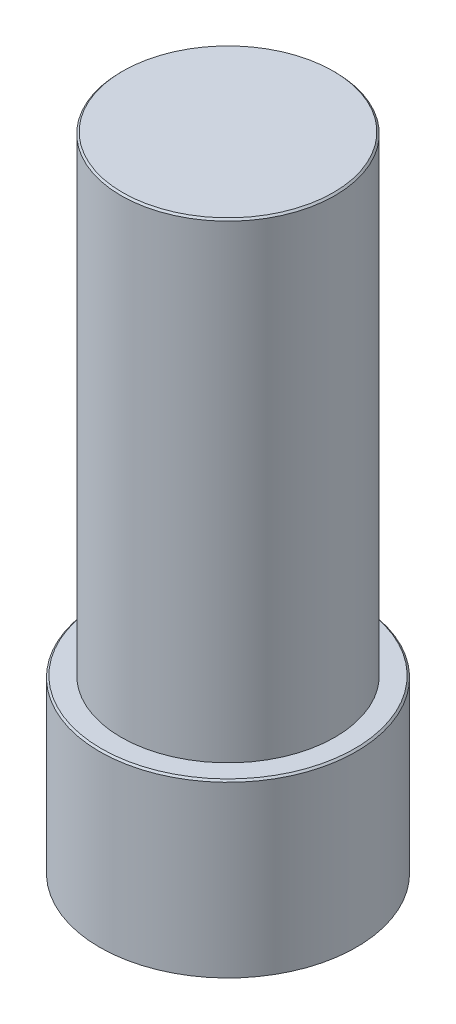
SolidWorks part; units mm, degrees
ref_plane "Plan de face" through (0, 0, 0) normal (0, 0, 1) x (1, 0, 0)
ref_plane "Plan de dessus" through (0, 0, 0) normal (0, 1, 0) x (1, 0, 0)
ref_plane "Plan de droite" through (0, 0, 0) normal (1, 0, 0) x (0, 0, -1)
sketch "Esquisse1" plane through (0, 0, 0) normal (0, 1, 0) x (1, 0, 0)
  circle A1 centre (0, 0) radius 15
  dimension "D1" = 30
extrude "Boss.-Extru.1" add sketch "Esquisse1" along normal blind 75
sketch "Esquisse2" plane through (0, 75, 0) normal (0, 1, 0) x (1, 0, 0)
  circle A0 centre (0, 0) radius 15
  circle A1 centre (0, 0) radius 12.5
extrude "Enlèv. mat.-Extru.1" cut sketch "Esquisse2" against normal blind 55
chamfer "Chanfrein4" distance 0.2 angle 45 1 edges at (0, 20, 15)
chamfer "Chanfrein5" distance 0.2 angle 45 1 edges at (0, 75, 12.5)
ref_plane "Plan1" through (0, 0, -12.5) normal (0, 0, -1) x (-1, 0, 0)
sketch "Esquisse3" plane through (0, 0, -12.5) normal (0, 0, -1) x (-1, 0, 0)
  line L0 (0, 70) -> (0, 45) construction
  line L1 (0, 55) -> (0, -55) construction
  line L2 (3.25, 70) -> (3.25, 45)
  line L3 (-3.25, 70) -> (-3.25, 45)
  line L4 (12.3, 75) -> (-12.3, 75) construction
  arc A0 (3.25, 70) -> (-3.25, 70) centre (0, 70) ccw
  arc A1 (-3.25, 45) -> (3.25, 45) centre (0, 45) ccw
  point P5 (0, 57.5)
  dimension "D3" = 3.25
  dimension "D1" = 25
  dimension "D2" = 5
extrude "Enlèv. mat.-Extru.2" cut sketch "Esquisse3" against normal blind 3
